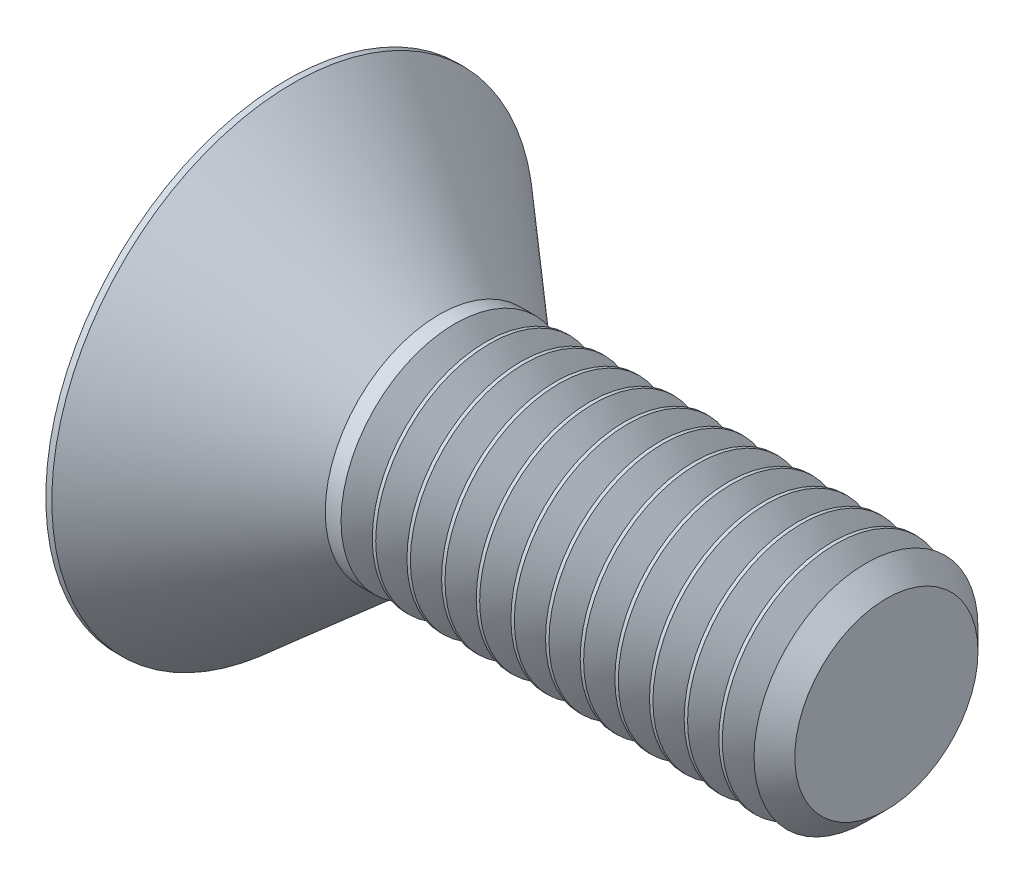
SolidWorks part; units mm, degrees
material "Chrome Stainless Steel"
ref_plane "Front Plane" through (0, 0, 0) normal (0, 0, 1) x (1, 0, 0)
ref_plane "Top Plane" through (0, 0, 0) normal (0, 1, 0) x (1, 0, 0)
ref_plane "Right Plane" through (0, 0, 0) normal (1, 0, 0) x (0, 0, -1)
sketch "Sketch1" plane through (0, 0, 0) normal (0, 0, 1) x (1, 0, 0)
  line L0 (0, 5.1067) -> (0, 0)
  line L1 (0, 0) -> (12.7, 0)
  line L2 (12.7, 0) -> (12.7, 1.9406)
  line L3 (12.7, 1.9406) -> (12.2683, 2.3723)
  line L4 (12.2683, 2.3723) -> (11.966, 1.9406)
  line L5 (11.966, 1.9406) -> (11.6352, 2.413)
  line L6 (11.6352, 2.413) -> (11.5627, 2.413)
  line L7 (11.5627, 2.413) -> (11.2319, 1.9406)
  line L8 (11.2319, 1.9406) -> (10.9011, 2.413)
  line L9 (10.9011, 2.413) -> (10.8286, 2.413)
  line L10 (10.8286, 2.413) -> (10.4978, 1.9406)
  line L11 (10.4978, 1.9406) -> (10.167, 2.413)
  line L12 (10.167, 2.413) -> (10.0946, 2.413)
  line L13 (10.0946, 2.413) -> (9.7638, 1.9406)
  line L14 (9.7638, 1.9406) -> (9.433, 2.413)
  line L15 (9.433, 2.413) -> (9.3605, 2.413)
  line L16 (9.3605, 2.413) -> (9.0297, 1.9406)
  line L17 (9.0297, 1.9406) -> (8.6989, 2.413)
  line L18 (8.6989, 2.413) -> (8.6264, 2.413)
  line L19 (8.6264, 2.413) -> (8.2956, 1.9406)
  line L20 (8.2956, 1.9406) -> (7.9648, 2.413)
  line L21 (7.9648, 2.413) -> (7.8924, 2.413)
  line L22 (7.8924, 2.413) -> (7.5616, 1.9406)
  line L23 (7.5616, 1.9406) -> (7.2307, 2.413)
  line L24 (7.2307, 2.413) -> (7.1583, 2.413)
  line L25 (7.1583, 2.413) -> (6.8275, 1.9406)
  line L26 (6.8275, 1.9406) -> (6.4967, 2.413)
  line L27 (6.4967, 2.413) -> (6.4242, 2.413)
  line L28 (6.4242, 2.413) -> (6.0934, 1.9406)
  line L29 (6.0934, 1.9406) -> (5.7626, 2.413)
  line L30 (5.7626, 2.413) -> (5.6902, 2.413)
  line L31 (5.6902, 2.413) -> (5.3594, 1.9406)
  line L32 (5.3594, 1.9406) -> (5.0285, 2.413)
  line L33 (5.0285, 2.413) -> (4.9561, 2.413)
  line L34 (4.9561, 2.413) -> (4.6253, 1.9406)
  line L35 (4.6253, 1.9406) -> (4.2945, 2.413)
  line L36 (4.2945, 2.413) -> (4.222, 2.413)
  line L37 (4.222, 2.413) -> (3.8912, 1.9406)
  line L38 (3.8912, 1.9406) -> (3.5604, 2.413)
  line L39 (3.5604, 2.413) -> (3.2257, 2.413)
  line L40 (3.2257, 2.413) -> (0.127, 5.1067)
  line L41 (0.127, 5.1067) -> (0, 5.1067)
  line L42 (0, 0) -> (12.7, 0) construction
revolve "Revolve1" add sketch "Sketch1" angle 360 about L42
sketch "Sketch2" plane through (0, 0, 0) normal (-1, 0, 0) x (0, 0, 1)
  line L0 (0, 1.8331) -> (-1.5875, 0.9165)
  line L1 (-1.5875, 0.9165) -> (-1.5875, -0.9165)
  line L2 (-1.5875, -0.9165) -> (0, -1.8331)
  line L3 (0, -1.8331) -> (1.5875, -0.9165)
  line L4 (1.5875, -0.9165) -> (1.5875, 0.9165)
  line L5 (1.5875, 0.9165) -> (0, 1.8331)
extrude "Cut-Extrude1" cut sketch "Sketch2" against normal blind 2.2098
sketch "Sketch3" plane through (0, 0, 0) normal (0, 0, 1) x (1, 0, 0)
  line L0 (2.2098, 1.5875) -> (2.2098, 0)
  line L1 (2.2098, 0) -> (3.1263, 0)
  line L2 (3.1263, 0) -> (2.2098, 1.5875)
  line L3 (2.2098, 0) -> (3.1264, 0) construction
revolve "Cut-Revolve1" cut sketch "Sketch3" angle 360 about L3
